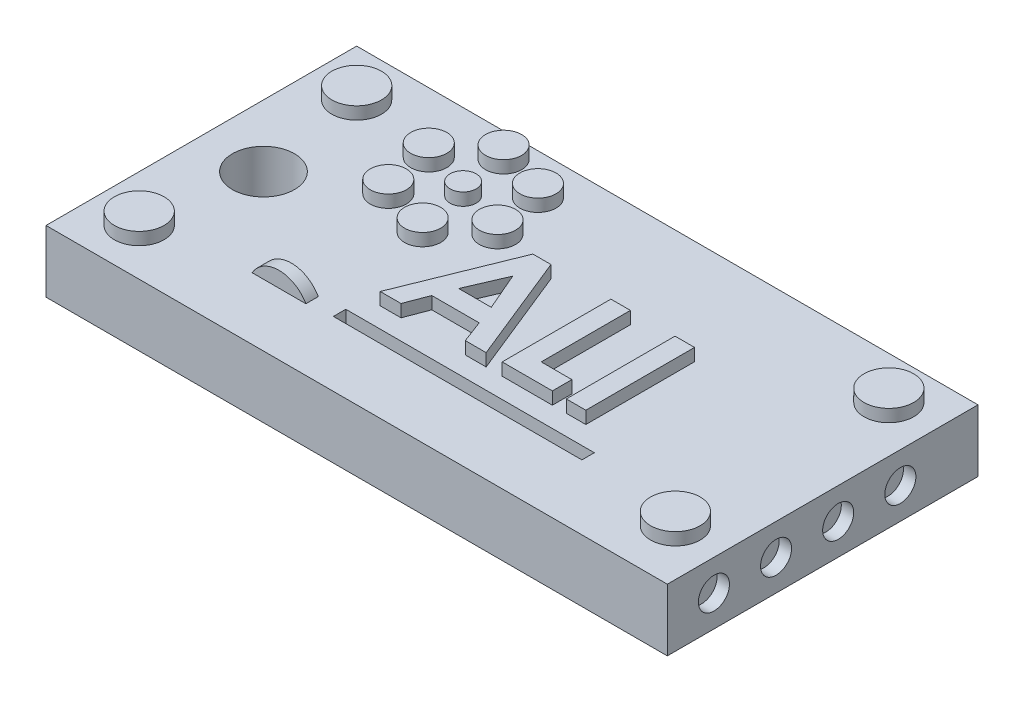
SolidWorks part; units mm, degrees
ref_plane "Front Plane" through (0, 0, 0) normal (0, 0, 1) x (1, 0, 0)
ref_plane "Top Plane" through (0, 0, 0) normal (0, 1, 0) x (1, 0, 0)
ref_plane "Right Plane" through (0, 0, 0) normal (1, 0, 0) x (0, 0, -1)
sketch "Sketch1" plane through (0, 0, 0) normal (0, 1, 0) x (1, 0, 0)
  line L1 (0, 0) -> (20, 0)
  line L2 (0, 0) -> (0, 10)
  line L3 (0, 10) -> (20, 10)
  line L4 (20, 0) -> (20, 10)
  circle A0 centre (2, 5) radius 1
  point P7 (1.9839, 5)
  dimension "D4" = 2
  dimension "D1" = 20
  dimension "D2" = 10
  dimension "D3" = 5
  dimension "D5" = 2
extrude "Boss-Extrude1" add sketch "Sketch1" along normal blind 2
sketch "Sketch2" plane through (0, 2, 0) normal (0, 1, 0) x (1, 0, 0)
  text T0 "<b>ALI</b>" font "Century Gothic" height 3.5
extrude "Boss-Extrude2" add sketch "Sketch2" along normal blind 0.4
sketch "Sketch4" plane through (0, 2, 0) normal (0, 1, 0) x (1, 0, 0)
  line L0 (0, 0) -> (20, 0) construction
  line L1 (7.1611, 2.4891) -> (15.1611, 2.4891)
  line L2 (7.1611, 2.4891) -> (7.1611, 2.0891)
  line L3 (7.1611, 2.0891) -> (15.1611, 2.0891)
  line L4 (15.1611, 2.4891) -> (15.1611, 2.0891)
  line L5 (20, 0) -> (20, 10) construction
  dimension "D1" = 0.4
  dimension "D2" = 8
  dimension "D3" = 2.0891
  dimension "D4" = 4.8389
extrude "Cut-Extrude4" cut sketch "Sketch4" against normal blind 0.4
sketch "Sketch5" plane through (0, 2, 0) normal (0, 1, 0) x (1, 0, 0)
  line L0 (0, 10) -> (0, 0) construction
  line L1 (20, 10) -> (0, 10) construction
  line L2 (20, 0) -> (20, 10) construction
  line L3 (0, 0) -> (20, 0) construction
  circle A0 centre (1.5, 8.5) radius 0.8
  circle A1 centre (18.5, 8.631) radius 0.8
  circle A2 centre (18.5, 1.7599) radius 0.8
  circle A3 centre (1.5, 1.5) radius 0.8
  point P8 (18.4139, 8.631)
  point P11 (18.2288, 1.7599)
  point P14 (1.5, 1.3279)
  point P15 (0, 0)
  point P16 (0, 0)
  point P19 (0, 0)
  dimension "D1" = 1.6
  dimension "D4" = 6.871
  dimension "D5" = 1.369
  dimension "D7" = 1.6
  dimension "D8" = 1.6
  dimension "D10" = 1.5
  dimension "D12" = 1.6
  dimension "D2" = 1.5
  dimension "D3" = 1.5
  dimension "D6" = 1.5
  dimension "D9" = 1.5
  dimension "D11" = 1.5
extrude "Boss-Extrude3" add sketch "Sketch5" along normal blind 0.4
sketch "Sketch6" plane through (0, 2, 0) normal (0, 1, 0) x (1, 0, 0)
  circle A0 centre (5.8838, 7.5429) radius 0.4203
sketch "Sketch7" plane through (0, 2, 0) normal (0, 1, 0) x (1, 0, 0)
  circle A0 centre (7.1451, 8.6905) radius 0.5817
extrude "Boss-Extrude4" add sketch "Sketch7" along normal blind 0.4
extrude "Boss-Extrude5" add sketch "Sketch6" along normal blind 0.4
pattern_circular "CirPattern1" count 6 over 360 about axis through (5.8838, 0, -7.5429) along (0, 1, 0) of "Boss-Extrude4"
sketch "Sketch8" plane through (20, 0, 0) normal (1, 0, 0) x (0, 0, -1)
  line L0 (0, 0) -> (10, 0) construction
  line L1 (0, 2) -> (0, 0) construction
  circle A0 centre (1.5, 1) radius 0.5
  point P2 (0, 0)
  point P3 (1.1736, 0.9994)
  dimension "D2" = 1
  dimension "D3" = 1.5
  dimension "D1" = 1
extrude "Cut-Extrude6" cut sketch "Sketch8" against normal blind 0.4
pattern_linear "LPattern1" count 4 spacing 2 along (0, 0, -1) of "Cut-Extrude6"
sketch "Sketch10" plane through (0, 0, 0) normal (0, 0, 1) x (1, 0, 0)
  line L0 (0, 2) -> (20, 2) construction
  line L1 (0, 2) -> (0, 0) construction
  circle A0 centre (5.5, 1.5) radius 1
  point P2 (0, 0)
  point P5 (0, 0)
  dimension "D1" = 2
  dimension "D2" = 0.5
  dimension "D3" = 5.5
extrude "Boss-Extrude6" add sketch "Sketch10" against normal blind 0.4 from offset 2
